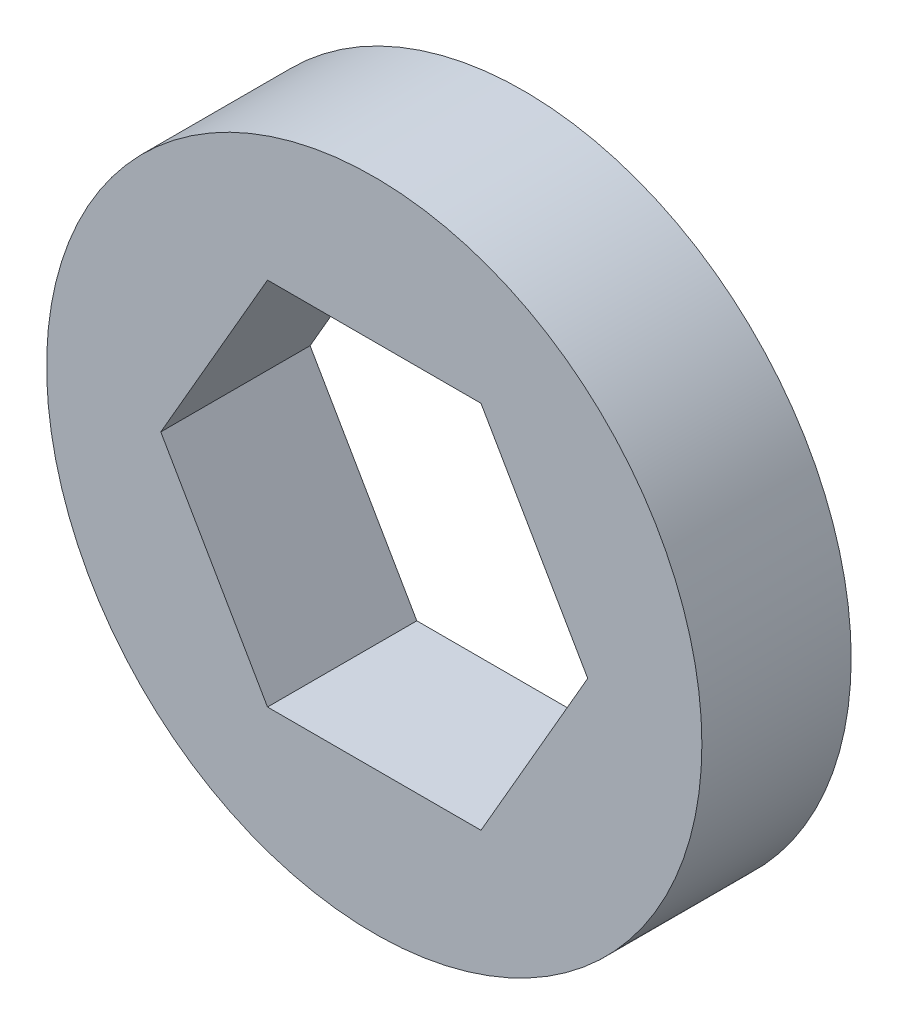
SolidWorks part; units mm, degrees
material "PET"
ref_plane "Front Plane" through (0, 0, 0) normal (0, 0, 1) x (1, 0, 0)
ref_plane "Top Plane" through (0, 0, 0) normal (0, 1, 0) x (1, 0, 0)
ref_plane "Right Plane" through (0, 0, 0) normal (1, 0, 0) x (0, 0, -1)
sketch "Sketch1" plane through (0, 0, 0) normal (0, 0, 1) x (1, 0, 0)
  line L1 (-5.7926, 0) -> (-2.8963, -5.0165)
  line L2 (-2.8963, -5.0165) -> (2.8963, -5.0165)
  line L3 (2.8963, -5.0165) -> (5.7926, 0)
  line L4 (5.7926, 0) -> (2.8963, 5.0165)
  line L5 (2.8963, 5.0165) -> (-2.8963, 5.0165)
  line L6 (-2.8963, 5.0165) -> (-5.7926, 0)
  circle A1 centre (0, 0) radius 8.89
  circle A2 centre (0, 0) radius 5.0165 construction
  point P1 (0, 0)
  point P11 (-5.7926, 0)
  point P12 (0, 0)
  dimension "D1" = 10.033
  dimension "D2" = 17.78
extrude "Boss-Extrude1" add sketch "Sketch1" along normal mid plane 4.0513
